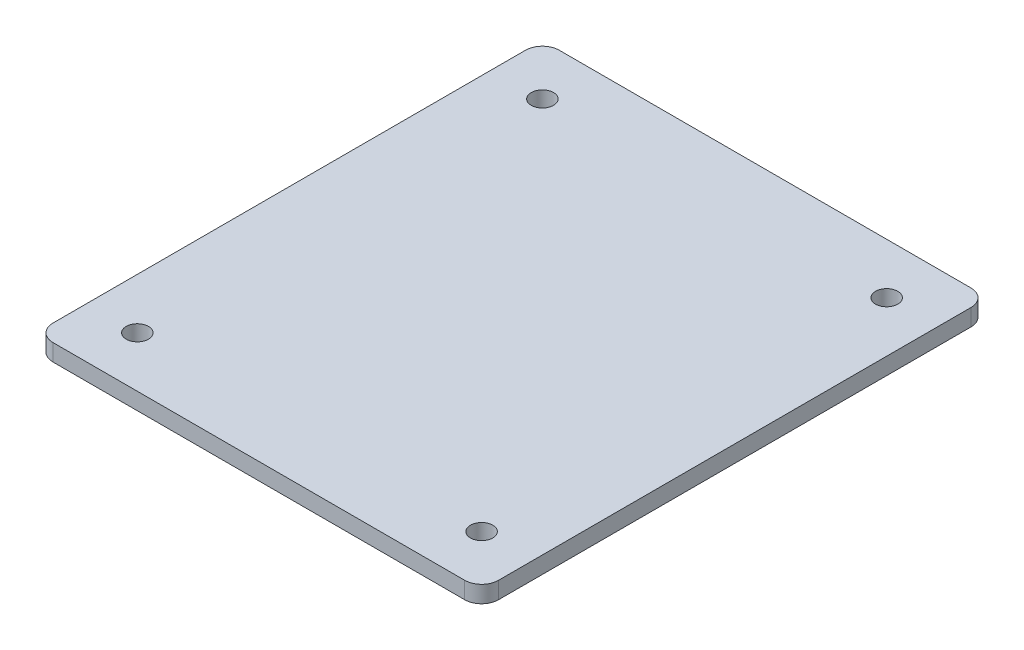
SolidWorks part; units mm, degrees
ref_plane "Front" through (0, 0, 0) normal (0, 0, 1) x (1, 0, 0)
ref_plane "Top" through (0, 0, 0) normal (0, 1, 0) x (1, 0, 0)
ref_plane "Right" through (0, 0, 0) normal (1, 0, 0) x (0, 0, -1)
sketch "Sketch1" plane through (0, 0, 0) normal (0, 1, 0) x (1, 0, 0)
  line L1 (0, 0) -> (132, 0)
  line L2 (0, 0) -> (0, 150)
  line L3 (0, 150) -> (132, 150)
  line L4 (132, 0) -> (132, 150)
  dimension "D1" = 132
  dimension "D2" = 150
extrude "Boss-Extrude1" add sketch "Sketch1" along normal blind 5
hole_wizard "M6 Clearance Hole1" positions "Sketch4" profile "Sketch5" hole size "M6" standard "ANSI Metric"
sketch "Sketch4" plane through (0, 0, 0) normal (0, -1, 0) x (-1, 0, 0)
  line L2 (-15, 15) -> (-117, 15) construction
  line L3 (-117, 15) -> (-117, 135) construction
  line L4 (-117, 135) -> (-15, 135) construction
  line L5 (-15, 135) -> (-15, 15) construction
  line L8 (0, 150) -> (0, 0) construction
  line L9 (-132, 150) -> (0, 150) construction
  point P0 (-15, 15)
  point P2 (-117, 15)
  point P4 (-117, 135)
  point P6 (-15, 135)
  point P19 (-15, 75)
  point P22 (0, 75)
  point P23 (-66, 135)
  point P26 (-66, 150)
  dimension "D1" = 120
  dimension "D2" = 102
sketch "Sketch5" plane through (15, 0, -15) normal (1, 0, 0) x (0, 0, -1)
  line L0 (0, 0) -> (0, 11.9828)
  line L1 (0, 11.9828) -> (3.3, 10)
  line L2 (3.3, 10) -> (3.3, 0)
  line L5 (3.3, 0) -> (0, 0)
  line L10 (0, 11.9828) -> (-3.3, 10) construction
  line L11 (0, -6.35) -> (0, 107.95) construction
  dimension "Hole Dia." = 6.6
  dimension "Hole Depth" = 10
  dimension "Drill Angle" = 118
fillet "Fillet1" radius 5 4 edges at (132, 2.5, -150) (132, 2.5, 0) (0, 2.5, 0) (0, 2.5, -150)
